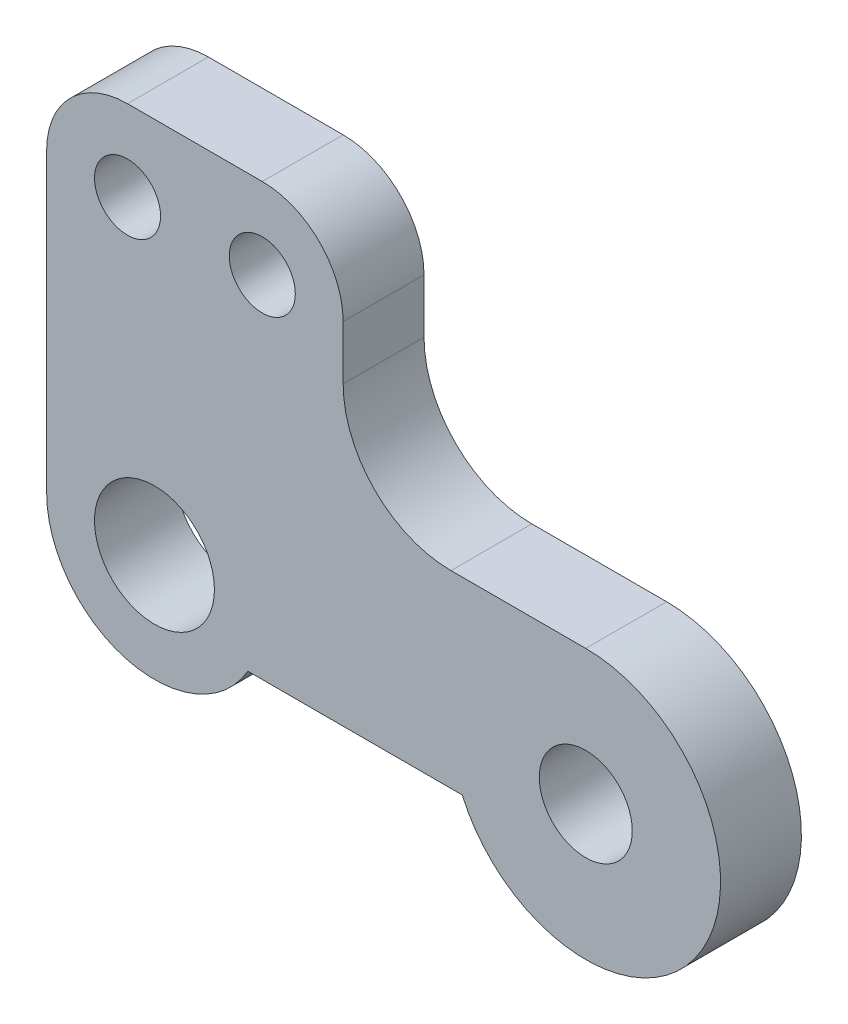
SolidWorks part; units mm, degrees
material "ABS"
ref_plane "Front Plane" through (0, 0, 0) normal (0, 0, 1) x (1, 0, 0)
ref_plane "Top Plane" through (0, 0, 0) normal (0, 1, 0) x (1, 0, 0)
ref_plane "Right Plane" through (0, 0, 0) normal (1, 0, 0) x (0, 0, -1)
sketch "Sketch1" plane through (0, 0, 0) normal (0, 0, 1) x (1, 0, 0)
  line L0 (3.4641, -2) -> (11.4174, -2)
  line L1 (7, 5) -> (16, 5)
  line L2 (-1, 14) -> (4, 14)
  line L4 (-4, 11) -> (-4, 0)
  line L5 (7, 11) -> (7, 5)
  arc A0 (-4, 0) -> (3.4641, -2) centre (0, 0) ccw
  circle A1 centre (0, 0) radius 2.225
  arc A2 (11.4174, -2) -> (16, 5) centre (16, 0) ccw
  circle A3 centre (16, 0) radius 1.725
  circle A4 centre (-1, 11) radius 1.225
  circle A5 centre (4, 11) radius 1.225
  arc A6 (-1, 14) -> (-4, 11) centre (-1, 11) ccw
  arc A7 (7, 11) -> (4, 14) centre (4, 11) ccw
  dimension "D1" = 8
  dimension "D2" = 3.45
  dimension "D4" = 16
  dimension "D5" = 2.45
  dimension "D8" = 6
  dimension "D9" = 11
  dimension "D10" = 4.45
  dimension "D11" = 5
  dimension "D3" = 2
  dimension "D6" = 5
extrude "Boss-Extrude1" add sketch "Sketch1" along normal blind 3
fillet "Fillet1" radius 4 1 edges at (7, 5, 1.5)
equation "\"D10@Sketch1\"=4+\"print_free@Parameters@FabricationParameters.sldprt\""
equation "\"D5@Sketch1\"=2.00mm+\"print_free@Parameters@FabricationParameters.sldprt\""
equation "\"D2@Sketch1\"=3+\"print_free@Parameters@FabricationParameters.sldprt\""
